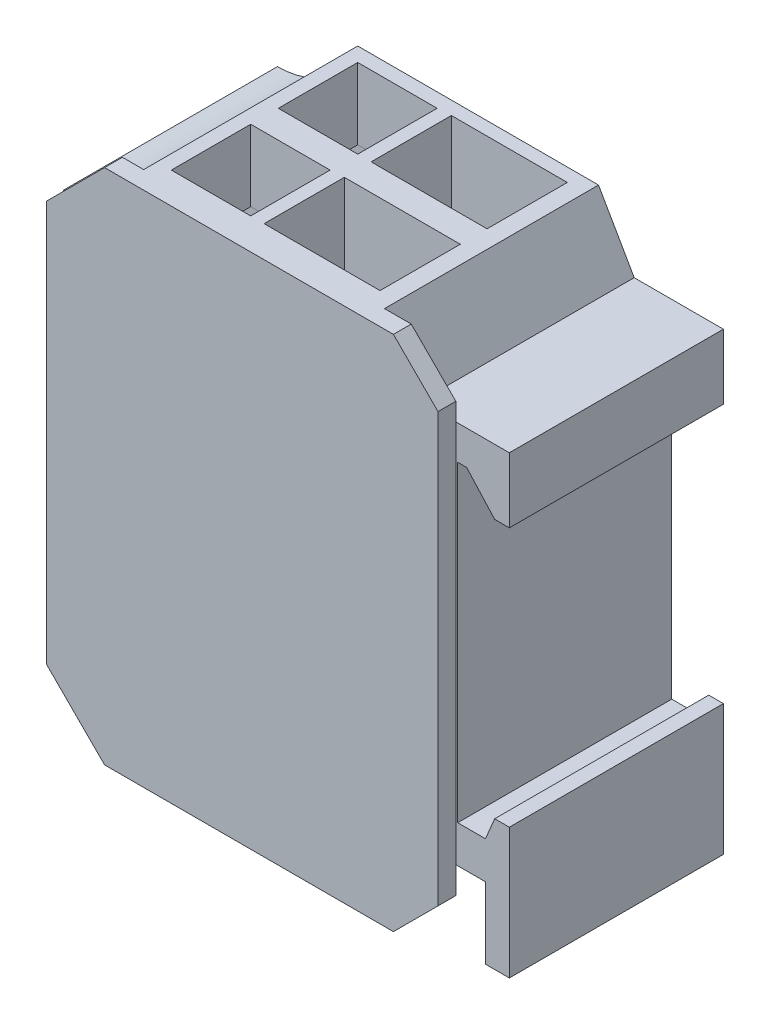
SolidWorks part; units mm, degrees
ref_plane "Спереди" through (0, 0, 0) normal (0, 0, 1) x (1, 0, 0)
ref_plane "Сверху" through (0, 0, 0) normal (0, 1, 0) x (1, 0, 0)
ref_plane "Справа" through (0, 0, 0) normal (1, 0, 0) x (0, 0, -1)
sketch "Эскиз1" plane through (0, 0, 0) normal (0, 0, 1) x (1, 0, 0)
  line L0 (53.7168, 100.3023) -> (49.7168, 107.2997)
  line L1 (22.7168, 49.2997) -> (49.7168, 49.2997)
  line L2 (58.9259, 96.4824) -> (57.9259, 96.4824)
  line L3 (22.7168, 107.2997) -> (43.7168, 107.2997)
  line L4 (63.7168, 57.2997) -> (63.7168, 63.9451)
  line L5 (13.7168, 67.7997) -> (13.7168, 55.7997)
  line L6 (61.0399, 57.2997) -> (49.7168, 57.2997)
  line L7 (63.7168, 100.3023) -> (53.7168, 100.3023)
  line L8 (17.2521, 71.7997) -> (17.2521, 84.7997)
  line L9 (13.7168, 67.7997) -> (17.2521, 71.7997)
  line L10 (62.0757, 93.0099) -> (58.9259, 96.4824)
  line L11 (17.2521, 84.7997) -> (13.7168, 88.7997)
  line L13 (63.7168, 63.9451) -> (62.0757, 63.9451)
  line L14 (62.0757, 63.9451) -> (61.0399, 61.4824)
  line L15 (63.7168, 93.0099) -> (62.0757, 93.0099)
  line L16 (63.7168, 57.2997) -> (63.7168, 49.2997)
  line L17 (49.7168, 57.2997) -> (49.7168, 49.2997)
  line L19 (13.7168, 100.7997) -> (13.7168, 88.7997)
  line L20 (63.7168, 93.0099) -> (63.7168, 100.3023)
  line L21 (63.7168, 49.2997) -> (61.0399, 49.2997)
  line L22 (61.0399, 57.2997) -> (61.0399, 49.2997)
  line L24 (43.7168, 107.2997) -> (49.7168, 107.2997)
  line L26 (61.0399, 61.4824) -> (57.9259, 61.4824)
  line L27 (57.9259, 96.4824) -> (57.9259, 61.4824)
  arc A0 (13.7168, 100.7997) -> (22.7168, 107.2997) centre (13.7168, 110.2805) ccw
  arc A1 (13.7168, 55.7997) -> (22.7168, 49.2997) centre (13.7168, 46.319) cw
  point P1 (63.7168, 107.2997)
  dimension "D10" = 12
  dimension "D7" = 10
  dimension "D2" = 45
  dimension "D3" = 58
  dimension "D4" = 6.5
  dimension "D6" = 35
  dimension "D8" = 8
  dimension "D9" = 14
  dimension "D5" = 12
  dimension "D11" = 13
  dimension "D13" = 50
  dimension "D16" = 1
extrude "Вытянуть2" add sketch "Эскиз1" along normal blind 24
sketch "Эскиз4" plane through (0, 107.2997, 0) normal (0, 1, 0) x (-1, 0, 0)
  line L1 (-49.7168, 24) -> (-22.7168, 24) construction
  line L2 (-49.7168, 0) -> (-22.7168, 0) construction
  line L3 (-49.7168, 24) -> (-49.7168, 0) construction
  line L5 (2.3057, 12) -> (-63.8154, 12) construction
  line L8 (-24.3154, 10.5) -> (-33.2168, 10.5)
  line L9 (-24.3154, 10.5) -> (-24.3154, 1.5986)
  line L10 (-24.3154, 1.5986) -> (-33.2168, 1.5986)
  line L11 (-33.2168, 10.5) -> (-33.2168, 1.5986)
  line L12 (-24.3154, 22.5) -> (-33.2168, 22.5)
  line L13 (-24.3154, 22.5) -> (-24.3154, 13.5986)
  line L14 (-24.3154, 13.5986) -> (-33.2168, 13.5986)
  line L15 (-47.7168, 13.5) -> (-34.7168, 13.5)
  line L16 (-47.7168, 13.5) -> (-47.7168, 22.5)
  line L17 (-47.7168, 22.5) -> (-34.7168, 22.5)
  line L18 (-34.7168, 13.5) -> (-34.7168, 22.5)
  line L19 (-47.7168, 1.5) -> (-34.7168, 1.5)
  line L20 (-47.7168, 1.5) -> (-47.7168, 10.5)
  line L21 (-47.7168, 10.5) -> (-34.7168, 10.5)
  line L22 (-34.7168, 1.5) -> (-34.7168, 10.5)
  line L23 (-33.2168, 22.5) -> (-33.2168, 13.5986)
  dimension "D1" = 13
  dimension "D2" = 2
  dimension "D3" = 1.5
  dimension "D4" = 9
  dimension "D5" = 1.5
  dimension "D6" = 1.5
extrude "Вырез-Вытянуть3" cut sketch "Эскиз4" against normal blind 15
sketch "Эскиз5" plane through (0, 92.2997, 0) normal (0, 1, 0) x (-1, 0, 0)
  line L0 (-41.2168, -1.8192) -> (-41.2168, 36.5335) construction
  line L1 (-31.3764, 6) -> (-48.6601, 6) construction
  line L2 (-31.3764, 18) -> (-49.9456, 18) construction
  line L3 (-34.7168, 1.5) -> (-34.7168, 10.5) construction
  line L4 (-47.7168, 10.5) -> (-47.7168, 1.5) construction
  line L5 (-34.7168, 10.5) -> (-47.7168, 10.5) construction
  line L6 (-47.7168, 1.5) -> (-34.7168, 1.5) construction
  line L7 (-34.7168, 22.5) -> (-47.7168, 22.5) construction
  line L8 (-47.7168, 13.5) -> (-34.7168, 13.5) construction
  circle A0 centre (-41.2168, 18) radius 2
  circle A1 centre (-41.2168, 6) radius 2
  dimension "D1" = 4
extrude "Вырез-Вытянуть4" cut sketch "Эскиз5" against normal blind 2
sketch "Эскиз6" plane through (0, 49.2997, 0) normal (0, -1, 0) x (1, 0, 0)
  line L0 (33.2168, 1.5986) -> (24.3154, 1.5986) construction
  line L1 (24.3154, 1.5986) -> (24.3154, 10.5) construction
  line L2 (24.3154, 10.5) -> (33.2168, 10.5) construction
  line L3 (33.2168, 10.5) -> (33.2168, 1.5986) construction
  line L4 (34.7168, 1.5) -> (34.7168, 10.5) construction
  line L5 (47.7168, 1.5) -> (34.7168, 1.5) construction
  line L6 (47.7168, 10.5) -> (47.7168, 1.5) construction
  line L7 (34.7168, 10.5) -> (47.7168, 10.5) construction
  line L8 (47.7168, 13.5) -> (34.7168, 13.5) construction
  line L9 (47.7168, 22.5) -> (47.7168, 13.5) construction
  line L10 (34.7168, 22.5) -> (47.7168, 22.5) construction
  line L11 (34.7168, 13.5) -> (34.7168, 22.5) construction
  line L12 (33.2168, 22.5) -> (33.2168, 13.5986) construction
  line L13 (24.3154, 22.5) -> (33.2168, 22.5) construction
  line L14 (24.3154, 13.5986) -> (24.3154, 22.5) construction
  line L15 (33.2168, 13.5986) -> (24.3154, 13.5986) construction
  line L16 (33.2168, 1.5986) -> (24.3154, 1.5986)
  line L17 (24.3154, 1.5986) -> (24.3154, 10.5)
  line L18 (24.3154, 10.5) -> (33.2168, 10.5)
  line L19 (33.2168, 10.5) -> (33.2168, 1.5986)
  line L20 (34.7168, 1.5) -> (34.7168, 10.5)
  line L21 (47.7168, 1.5) -> (34.7168, 1.5)
  line L22 (47.7168, 10.5) -> (47.7168, 1.5)
  line L23 (34.7168, 10.5) -> (47.7168, 10.5)
  line L24 (47.7168, 13.5) -> (34.7168, 13.5)
  line L25 (47.7168, 22.5) -> (47.7168, 13.5)
  line L26 (34.7168, 22.5) -> (47.7168, 22.5)
  line L27 (34.7168, 13.5) -> (34.7168, 22.5)
  line L28 (33.2168, 22.5) -> (33.2168, 13.5986)
  line L29 (24.3154, 22.5) -> (33.2168, 22.5)
  line L30 (24.3154, 13.5986) -> (24.3154, 22.5)
  line L31 (33.2168, 13.5986) -> (24.3154, 13.5986)
extrude "Вырез-Вытянуть5" cut sketch "Эскиз6" against normal blind 15
sketch "Эскиз7" plane through (13.7168, 0, 0) normal (-1, 0, 0) x (0, 0, 1)
  line L0 (12, 110.2902) -> (12, 48.7691) construction
  line L1 (24, 84.7997) -> (24, 71.7997) construction
  line L2 (0, 84.7997) -> (0, 71.7997) construction
  line L3 (31.9264, 78.2997) -> (-6.9037, 78.2997) construction
  line L4 (13.5, 99.2997) -> (22.5, 99.2997)
  line L5 (13.5, 99.2997) -> (13.5, 90.2997)
  line L6 (13.5, 90.2997) -> (22.5, 90.2997)
  line L7 (22.5, 99.2997) -> (22.5, 90.2997)
  line L8 (13.5, 66.2997) -> (22.5, 66.2997)
  line L9 (13.5, 66.2997) -> (13.5, 57.2997)
  line L10 (13.5, 57.2997) -> (22.5, 57.2997)
  line L11 (22.5, 66.2997) -> (22.5, 57.2997)
  line L12 (1.5, 99.2997) -> (10.5, 99.2997)
  line L13 (1.5, 99.2997) -> (1.5, 90.2997)
  line L14 (1.5, 90.2997) -> (10.5, 90.2997)
  line L15 (10.5, 99.2997) -> (10.5, 90.2997)
  line L16 (1.5, 66.2997) -> (10.5, 66.2997)
  line L17 (1.5, 66.2997) -> (1.5, 57.2997)
  line L18 (1.5, 57.2997) -> (10.5, 57.2997)
  line L19 (10.5, 66.2997) -> (10.5, 57.2997)
  line L20 (24, 100.7997) -> (0, 100.7997) construction
  line L21 (24, 55.7997) -> (0, 55.7997) construction
  line L23 (1.5, 70.7529) -> (10.5, 70.7529)
  line L24 (1.5, 70.7529) -> (1.5, 89.3049)
  line L25 (1.5, 89.3049) -> (10.5, 89.3049)
  line L26 (10.5, 70.7529) -> (10.5, 89.3049)
  line L27 (13.5, 70.7529) -> (22.5, 70.7529)
  line L28 (13.5, 70.7529) -> (13.5, 89.3049)
  line L29 (13.5, 89.3049) -> (22.5, 89.3049)
  line L30 (22.5, 70.7529) -> (22.5, 89.3049)
  dimension "D1" = 3
  dimension "D2" = 3
  dimension "D3" = 9
  dimension "D4" = 1.5
extrude "Вырез-Вытянуть6" cut sketch "Эскиз7" against normal blind 15
sketch "Эскиз8" plane through (0, 0, 24) normal (0, 0, 1) x (1, 0, 0)
  line L0 (22.7168, 49.2997) -> (49.7168, 49.2997) construction
  line L1 (20.3317, 49.2997) -> (52.7169, 49.2997)
  line L2 (13.8317, 55.7997) -> (13.8317, 100.7997)
  line L3 (20.3317, 107.2997) -> (52.7169, 107.2997)
  line L4 (57.7169, 54.2997) -> (57.7169, 102.2997)
  line L5 (49.7168, 107.2997) -> (22.7168, 107.2997) construction
  line L6 (52.7169, 107.2997) -> (57.7169, 102.2997)
  line L7 (52.7169, 49.2997) -> (57.7169, 54.2997)
  line L8 (13.8317, 100.7997) -> (20.3317, 107.2997)
  line L9 (13.8317, 55.7997) -> (20.3317, 49.2997)
  point P0 (13.8317, 49.2997)
  point P1 (57.7169, 107.2997)
  point P2 (13.8317, 107.2997)
  point P3 (57.7169, 49.2997)
  dimension "D3" = 5
  dimension "D4" = 5
  dimension "D5" = 6.5
  dimension "D10" = 6.5
extrude "Вытянуть3" add sketch "Эскиз8" along normal blind 2
